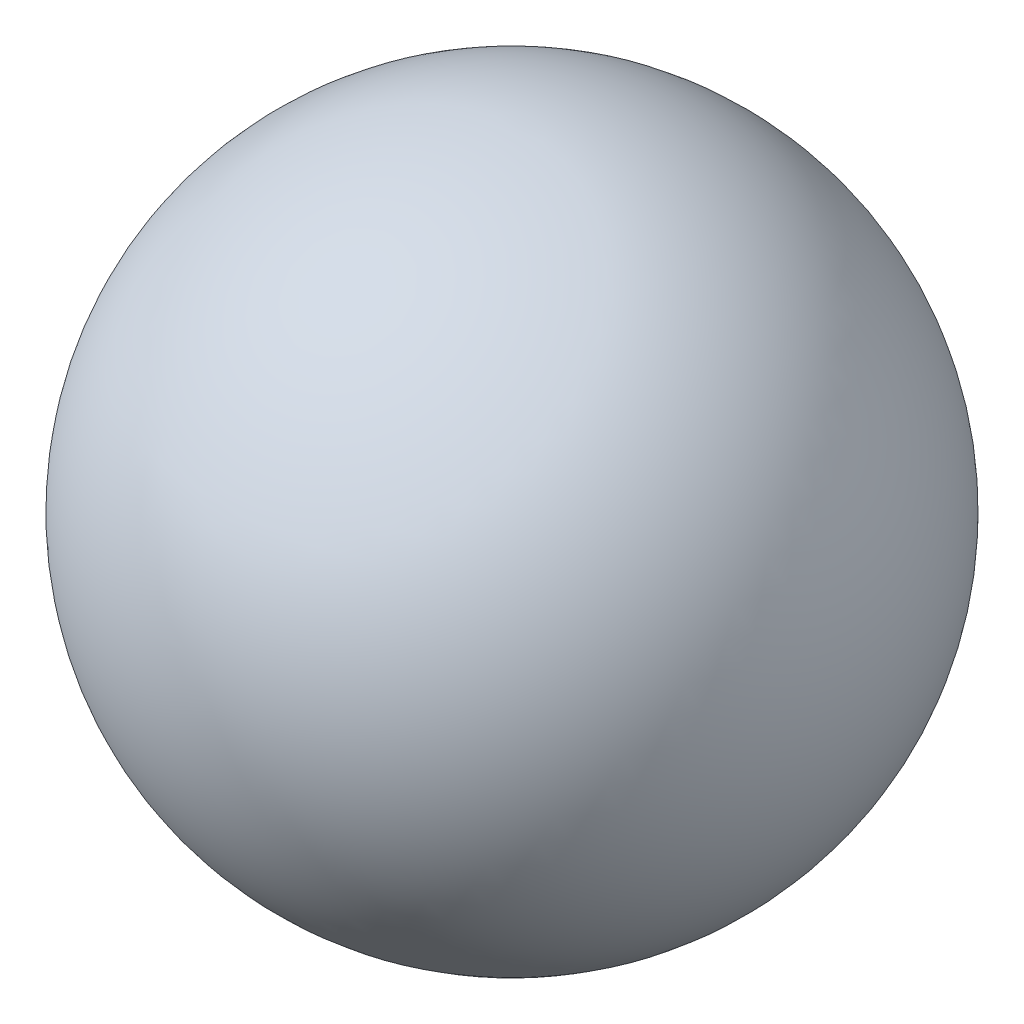
SolidWorks part; units mm, degrees
material "Plain Carbon Steel"
ref_plane "Front Plane" through (0, 0, 0) normal (0, 0, 1) x (1, 0, 0)
ref_plane "Top Plane" through (0, 0, 0) normal (0, 1, 0) x (1, 0, 0)
ref_plane "Right Plane" through (0, 0, 0) normal (1, 0, 0) x (0, 0, -1)
sketch "Sketch1" plane through (0, 0, 0) normal (0, 1, 0) x (1, 0, 0)
  line L0 (0, 26.2015) -> (0, -30.3116) construction
  line L1 (0, 20) -> (0, -20)
  arc A0 (0, -20) -> (0, 20) centre (0, 0) ccw
  dimension "D1" = 40
revolve "Revolve1" add sketch "Sketch1" angle 360 about L1
sketch "Sketch2" plane through (0, 0, 0) normal (1, 0, 0) x (0, 0, -1)
  line L0 (-8.7178, -18) -> (8.7178, -18)
  circle A0 centre (0, 0) radius 20 construction
  dimension "D1" = 38
extrude "Cut-Extrude2" cut sketch "Sketch2" against normal through all both and the other way through all flip side to cut
hole_wizard "M10 Tapped Hole1" positions "Sketch3" profile "Sketch4" tap size "M10" standard "DIN"
sketch "Sketch3" plane through (0, -18, 0) normal (0, -1, 0) x (-1, 0, 0)
  point P0 (0, 0)
sketch "Sketch4" plane through (0, -18, 0) normal (1, 0, 0) x (0, 0, -1)
  line L0 (0, 0) -> (0, 12.5537)
  line L1 (0, 12.5537) -> (4.25, 10)
  line L2 (4.25, 10) -> (4.25, 0)
  line L5 (4.25, 0) -> (0, 0)
  line L10 (0, 12.5537) -> (-4.25, 10) construction
  line L11 (0, -6.35) -> (0, 107.95) construction
  dimension "Tap Drill Dia." = 8.5
  dimension "Tap Drill Depth" = 10
  dimension "Drill Angle" = 118
cosmetic thread "Hole Thread1" parameters "D1"=10, "D2"=10
